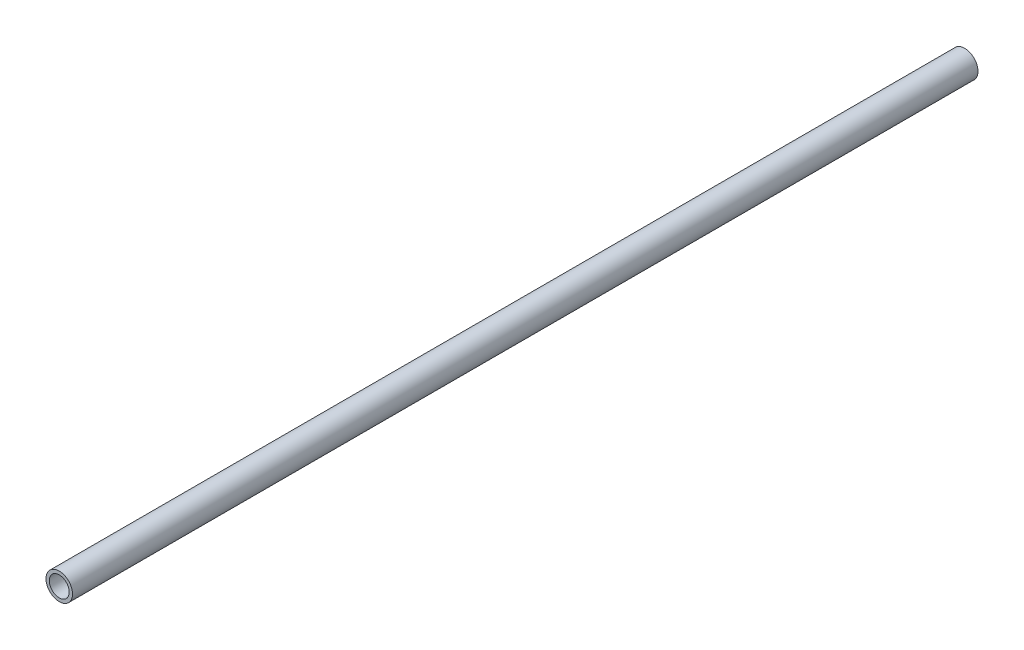
SolidWorks part; units mm, degrees
material "Thornel Mat VMA"
ref_plane "Front Plane" through (0, 0, 0) normal (0, 0, 1) x (1, 0, 0)
ref_plane "Top Plane" through (0, 0, 0) normal (0, 1, 0) x (1, 0, 0)
ref_plane "Right Plane" through (0, 0, 0) normal (1, 0, 0) x (0, 0, -1)
sketch "Sketch1" plane through (0, 0, 0) normal (0, 0, 1) x (1, 0, 0)
  circle A0 centre (0, 0) radius 2
  circle A1 centre (0, 0) radius 1.5
  dimension "D1" = 4
  dimension "D2" = 3
extrude "Boss-Extrude1" add sketch "Sketch1" along normal blind 136.398
